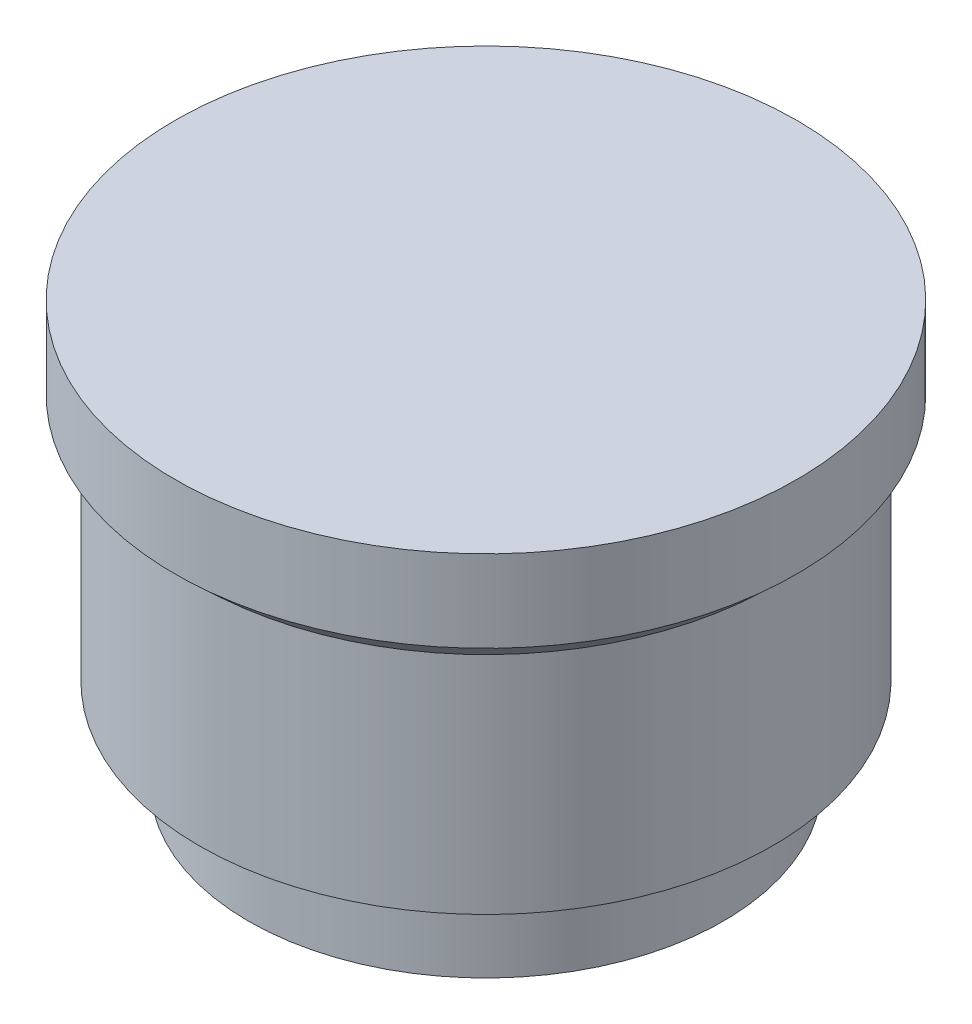
SolidWorks part; units mm, degrees
ref_plane "Front Plane" through (0, 0, 0) normal (0, 0, 1) x (1, 0, 0)
ref_plane "Top Plane" through (0, 0, 0) normal (0, 1, 0) x (1, 0, 0)
ref_plane "Right Plane" through (0, 0, 0) normal (1, 0, 0) x (0, 0, -1)
sketch "Sketch1" plane through (0, 0, 0) normal (0, 0, 1) x (1, 0, 0)
  line L0 (0, -13.5651) -> (0, 25.2854) construction
  line L1 (-29, 0) -> (0, 0)
  line L2 (0, 10.9641) -> (-35, 10.9641) construction
  line L3 (0, 51.25) -> (-38, 51.25)
  line L4 (-29, 0) -> (-29, 7.5)
  line L5 (-29, 7.5) -> (-35, 10.9641)
  line L6 (-29, 7.5) -> (-51.0316, 7.5) construction
  line L7 (-35, 10.9641) -> (-35, 38.4641)
  line L8 (-38, 51.25) -> (-38, 41.25)
  line L9 (-38, 41.25) -> (-35, 38.4641)
  line L10 (0, 51.25) -> (0, 0)
  dimension "D1" = 51.25
  dimension "D2" = 29
  dimension "D3" = 7.5
  dimension "D4" = 30
  dimension "D5" = 35
  dimension "D6" = 27.5
  dimension "D7" = 38
  dimension "D8" = 10
revolve "Revolve1" add sketch "Sketch1" angle 360 about L0
